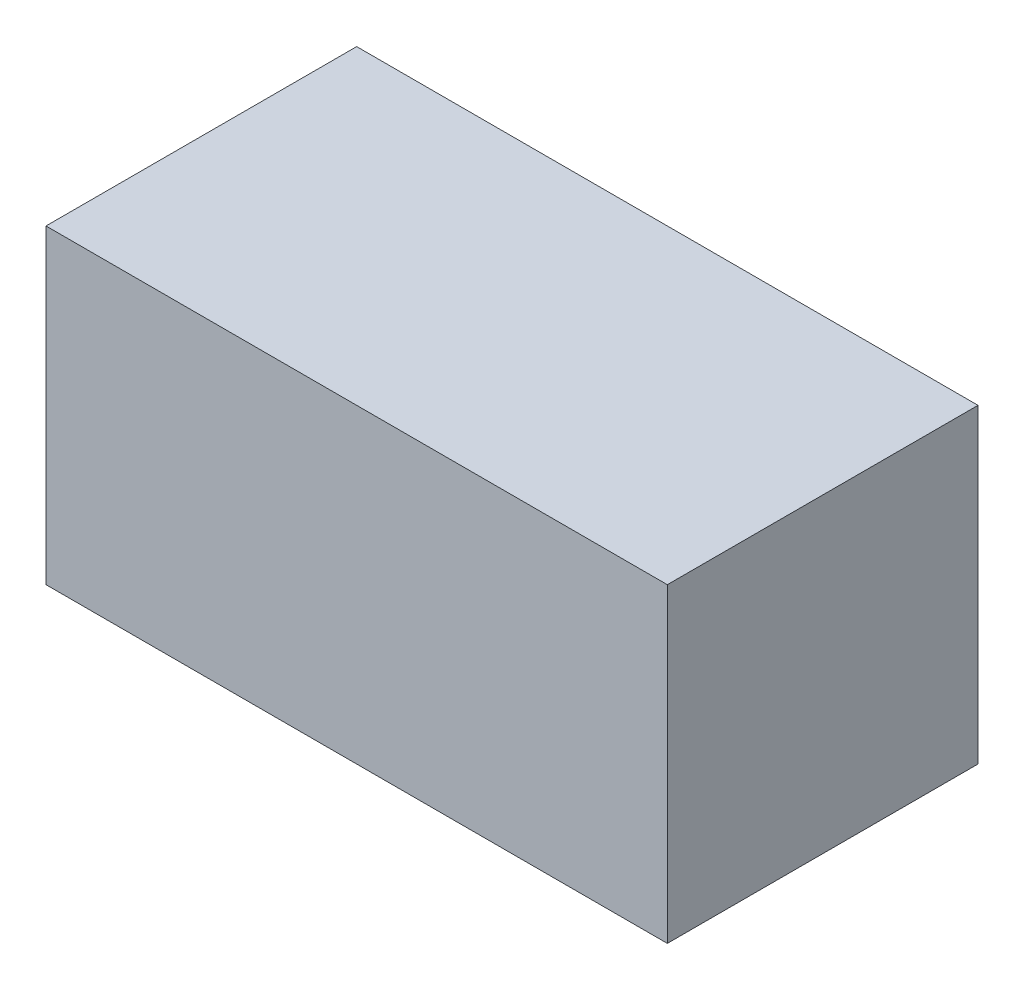
SolidWorks part; units mm, degrees
ref_plane "Front Plane" through (0, 0, 0) normal (0, 0, 1) x (1, 0, 0)
ref_plane "Top Plane" through (0, 0, 0) normal (0, 1, 0) x (1, 0, 0)
ref_plane "Right Plane" through (0, 0, 0) normal (1, 0, 0) x (0, 0, -1)
sketch "Sketch1" plane through (0, 0, 0) normal (0, 1, 0) x (1, 0, 0)
  line L0 (0, 0) -> (-45, 0)
  line L1 (-45, 0) -> (-45, 45)
  line L2 (-45, 45) -> (9.6729, 45)
  line L3 (9.6729, 45) -> (45, 45)
  line L4 (45, 45) -> (45, 0)
  line L5 (45, 0) -> (0, 0)
  dimension "D2" = 45
  dimension "D3" = 45
extrude "Boss-Extrude1" add sketch "Sketch1" along normal blind 45
sketch "Sketch2" plane through (0, 45, 0) normal (0, 1, 0) x (1, 0, 0)
  circle A0 centre (-1.0225, 26.8005) radius 21.773
